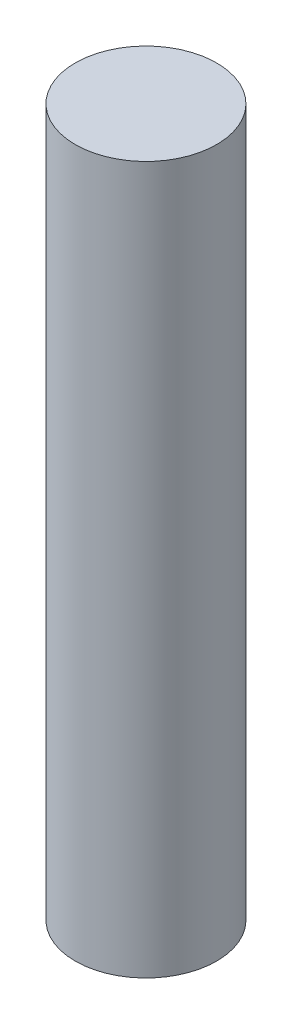
SolidWorks part; units mm, degrees
material "AISI 316 Stainless Steel Sheet (SS)"
ref_plane "Front" through (0, 0, 0) normal (0, 0, 1) x (1, 0, 0)
ref_plane "Top" through (0, 0, 0) normal (0, 1, 0) x (1, 0, 0)
ref_plane "Right" through (0, 0, 0) normal (1, 0, 0) x (0, 0, -1)
sketch "Sketch1" plane through (0, 0, 0) normal (0, 1, 0) x (1, 0, 0)
  circle A0 centre (0, 0) radius 1.5875
  dimension "D1" = 3.175
extrude "Boss-Extrude1" add sketch "Sketch1" along normal blind 15.875
